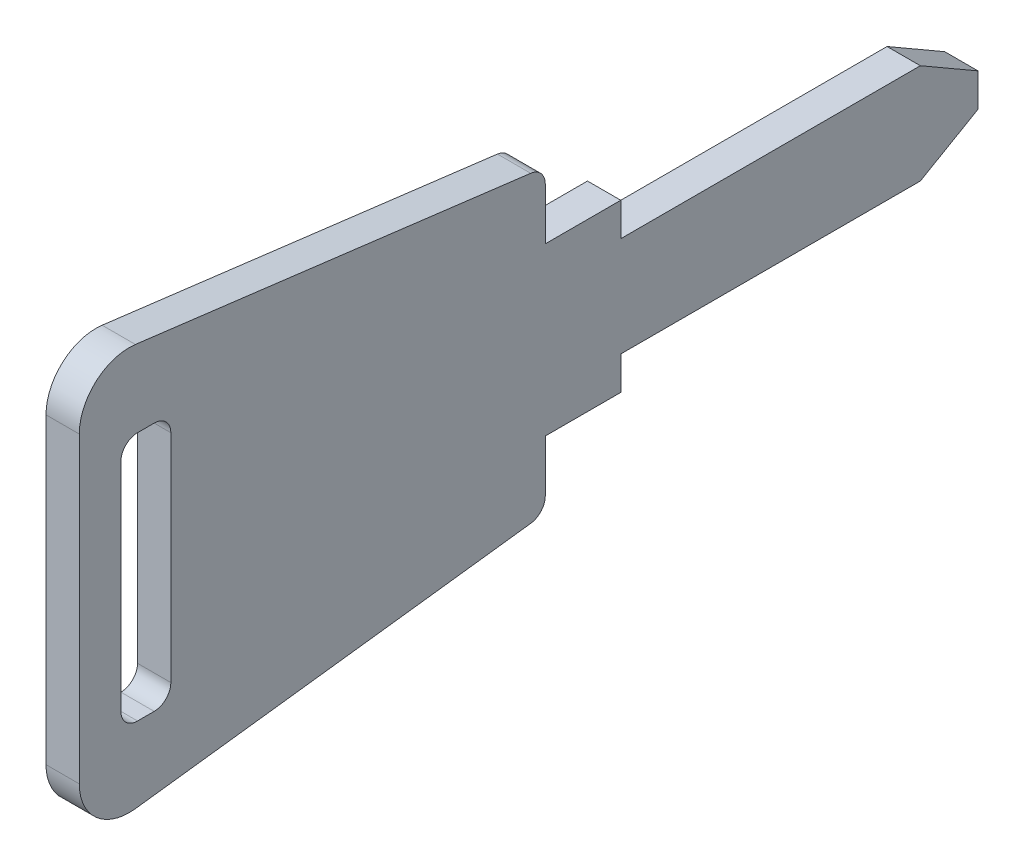
SolidWorks part; units mm, degrees
ref_plane "Front Plane" through (0, 0, 0) normal (0, 0, 1) x (1, 0, 0)
ref_plane "Top Plane" through (0, 0, 0) normal (0, 1, 0) x (1, 0, 0)
ref_plane "Right Plane" through (0, 0, 0) normal (1, 0, 0) x (0, 0, -1)
sketch "Sketch1" plane through (0, 0, 0) normal (1, 0, 0) x (0, 0, -1)
  line L0 (0, -9.1017) -> (0, 9.1017)
  line L1 (3.3721, 12.0785) -> (27.124, 9.1095)
  line L2 (28, 8.1172) -> (28, 5)
  line L3 (28, 5) -> (32.5359, 5)
  line L4 (32.5359, 5) -> (32.5359, 3)
  line L5 (32.5359, 3) -> (50.5359, 3)
  line L6 (50.5359, 3) -> (54, 1)
  line L7 (54, 1) -> (54, -1)
  line L8 (0, 0) -> (54, 0)
  line L9 (50.5359, -3) -> (54, -1)
  line L10 (32.5359, -3) -> (50.5359, -3)
  line L11 (32.5359, -5) -> (32.5359, -3)
  line L12 (28, -5) -> (32.5359, -5)
  line L13 (28, -8.1172) -> (28, -5)
  line L14 (3.3721, -12.0785) -> (27.124, -9.1095)
  arc A0 (3.3721, 12.0785) -> (0, 9.1017) centre (3, 9.1017) ccw
  arc A1 (27.124, 9.1095) -> (28, 8.1172) centre (27, 8.1172) cw
  arc A2 (27.124, -9.1095) -> (28, -8.1172) centre (27, -8.1172) ccw
  arc A3 (3.3721, -12.0785) -> (0, -9.1017) centre (3, -9.1017) cw
  point P12 (0, 12.5)
  point P15 (28, 9)
  point P27 (28, -9)
  point P28 (0, -12.5)
  dimension "D10" = 3
  dimension "D11" = 1
  dimension "D1" = 28
  dimension "D2" = 2
  dimension "D3" = 12.5
  dimension "D4" = 4
  dimension "D5" = 54
  dimension "D6" = 18
  dimension "D7" = 1
  dimension "D8" = 150
  dimension "D9" = 9
extrude "Boss-Extrude1" add sketch "Sketch1" along normal blind 2 contours A1 L1 A0 L0 L8 L7 L6 L5 L4 L3 L2 | A3 L14 A2 L13 L12 L11 L10 L9 L7 L8 L0
sketch "Sketch2" plane through (2, 0, 0) normal (1, 0, 0) x (0, 0, -1)
  line L0 (0, -9.1017) -> (0, 9.1017) construction
  line L1 (4.5, -7.5785) -> (3.5, -7.5785)
  line L2 (5.5, -6.5785) -> (5.5, 6.4215)
  line L3 (4.5, 7.4215) -> (3.5, 7.4215)
  line L4 (2.5, -6.5785) -> (2.5, 6.4215)
  line L5 (5.5, -7.5785) -> (2.5, 7.4215) construction
  line L6 (5.5, 7.4215) -> (2.5, -7.5785) construction
  arc A0 (5.5, -6.5785) -> (4.5, -7.5785) centre (4.5, -6.5785) cw
  arc A1 (2.5, -6.5785) -> (3.5, -7.5785) centre (3.5, -6.5785) ccw
  arc A2 (5.5, 6.4215) -> (4.5, 7.4215) centre (4.5, 6.4215) ccw
  arc A3 (3.5, 7.4215) -> (2.5, 6.4215) centre (3.5, 6.4215) ccw
  point P0 (4, -0.0785)
  dimension "D5" = 1
  dimension "D1" = 3
  dimension "D2" = 15
  dimension "D3" = 4.5
  dimension "D4" = 2.5
extrude "Cut-Extrude1" cut sketch "Sketch2" against normal through all
